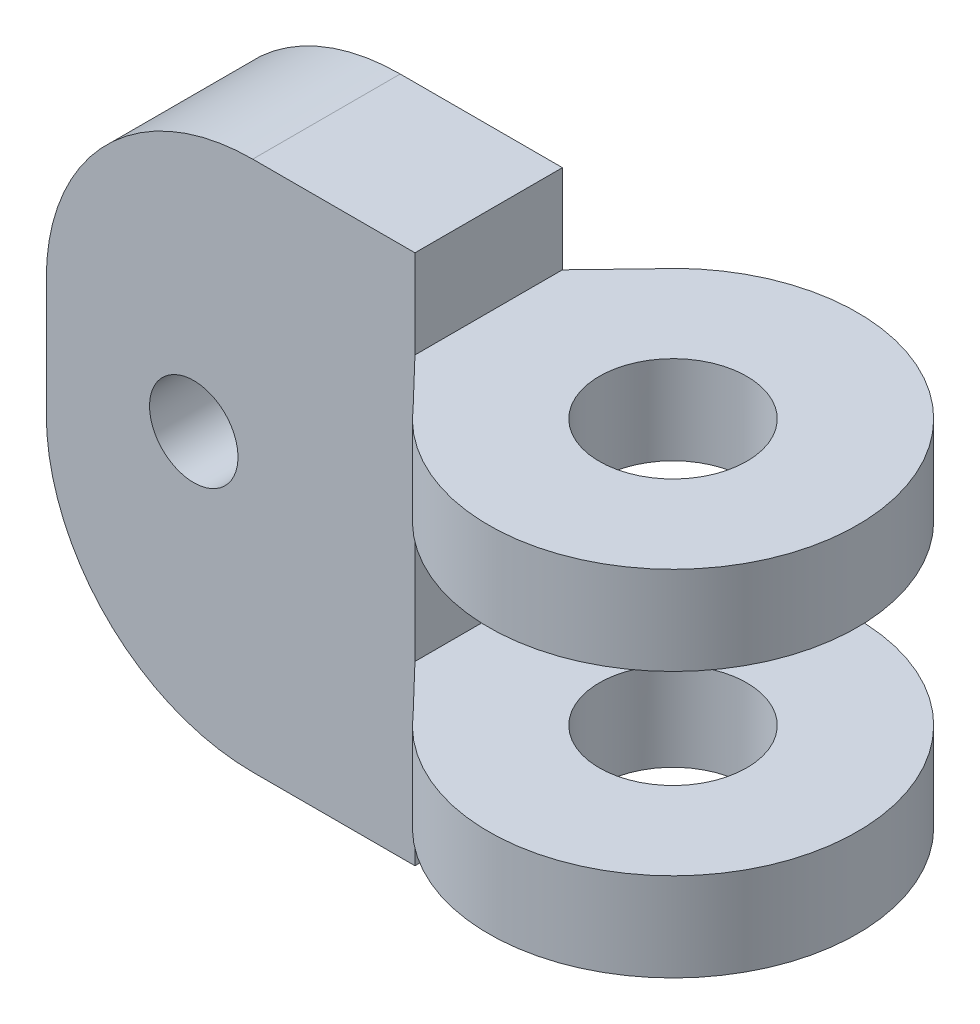
SolidWorks part; units mm, degrees
ref_plane "Alzado" through (0, 0, 0) normal (0, 0, 1) x (1, 0, 0)
ref_plane "Planta" through (0, 0, 0) normal (0, 1, 0) x (1, 0, 0)
ref_plane "Vista lateral" through (0, 0, 0) normal (1, 0, 0) x (0, 0, -1)
sketch "Croquis1" plane through (0, 0, 0) normal (0, 0, 1) x (1, 0, 0)
  line L0 (11.25, 17.1) -> (11.25, 14.1)
  line L1 (5.75, -0.9) -> (11.25, -0.9)
  line L2 (-1.25, 6.1) -> (-1.25, 10.1)
  line L3 (5.75, 17.1) -> (11.25, 17.1)
  line L4 (11.25, 11.1) -> (23.75, 11.1)
  line L5 (-1.25, -0.9) -> (1.25, 0.9) construction
  line L6 (-1.25, 17.1) -> (-1.0254, 14.0276) construction
  line L7 (11.25, 11.1) -> (11.25, 5.1)
  line L8 (-1.25, 8.1) -> (23.75, 8.1) construction
  line L9 (23.75, 5.1) -> (11.25, 5.1)
  line L10 (11.25, 2.1) -> (11.25, -0.9)
  line L11 (23.75, 11.1) -> (23.75, 14.1)
  line L12 (23.75, 14.1) -> (11.25, 14.1)
  line L13 (11.25, 17.1) -> (-1.25, 17.1) construction
  line L14 (23.75, 5.1) -> (23.75, 2.1)
  line L15 (23.75, 2.1) -> (11.25, 2.1)
  circle A0 centre (3.75, 8.1) radius 1.5
  arc A1 (-1.25, 10.1) -> (5.75, 17.1) centre (5.75, 10.1) cw
  arc A2 (5.75, -0.9) -> (-1.25, 6.1) centre (5.75, 6.1) cw
  point P0 (0, 0)
  dimension "D6" = 3
  dimension "D4" = 7
  dimension "D2" = 18
  dimension "D3" = 12.5
  dimension "D7" = 5
  dimension "D8" = 9
  dimension "D10" = 3
  dimension "D11" = 3
extrude "Saliente-Extruir1" add sketch "Croquis1" along normal blind 15
sketch "Croquis2" plane through (0, 0, 0) normal (0, 1, 0) x (1, 0, 0)
  line L0 (23.75, -7.5) -> (11.25, -7.5) construction
  line L1 (23.75, -7.5) -> (11.25, -7.5) construction
  line L2 (23.75, -15) -> (23.75, 0) construction
  line L3 (17.5, -1.25) -> (11.25, 0)
  line L4 (17.5, -13.75) -> (11.25, -15)
  line L5 (11.25, -15) -> (11.25, -17.9613)
  line L6 (11.25, -17.9613) -> (29.6635, -17.9613)
  line L7 (29.6635, -17.9613) -> (29.6635, 1.8686)
  line L8 (29.6635, 1.8686) -> (11.1263, 1.8686)
  line L9 (11.1263, 1.8686) -> (11.25, 0)
  line L10 (11.25, -15) -> (11.25, 0) construction
  line L11 (17.5, 0) -> (17.5, -15) construction
  line L12 (23.75, 0) -> (11.25, 0) construction
  line L13 (23.75, -15) -> (11.25, -15) construction
  circle A0 centre (17.5, -7.5) radius 2.5
  arc A1 (17.5, -13.75) -> (17.5, -1.25) centre (17.5, -7.5) ccw
  dimension "D1" = 5
extrude "Cortar-Extruir1" cut sketch "Croquis2" along normal blind 20
sketch "Croquis4" plane through (0, 17.1, 0) normal (0, 1, 0) x (1, 0, 0)
  line L0 (17.5, -1.25) -> (17.5, -13.75) construction
  line L1 (-1.25, -15) -> (-1.25, 0) construction
  line L2 (-4.3896, -10) -> (11.25, -10)
  line L4 (-4.3896, -5) -> (11.25, -5)
  line L5 (17.5, -1.25) -> (17.5, 1.8877)
  line L8 (11.25, -15) -> (11.25, 0) construction
  line L9 (11.25, -5) -> (13.2786, -2.891)
  line L10 (11.25, -10) -> (12.7402, -11.5505)
  line L11 (17.5, 1.8877) -> (-4.3896, 1.8877)
  line L12 (-4.3896, 1.8877) -> (-4.3896, -5)
  line L13 (-4.3896, -10) -> (-4.3896, -16.4565)
  line L14 (-4.3896, -16.4565) -> (17.5, -16.4565)
  line L15 (17.5, -16.4565) -> (17.5, -13.75)
  arc A0 (12.7402, -11.5505) -> (17.5, -13.75) centre (17.5, -7.5) ccw
  arc A1 (17.5, -1.25) -> (12.7307, -3.4607) centre (17.5, -7.5) ccw
  point P6 (-1.25, -7.5)
  line M1 (11.25, 0) -> (5.75, 0)
  line M2 (5.75, 0) -> (5.75, -15)
  line M3 (5.75, -15) -> (11.25, -15)
  line M4 (11.25, -15) -> (11.25, 0)
  dimension "D1" = 5
extrude "Cortar-Extruir2" cut sketch "Croquis4" against normal blind 26 contours A1 L5 L11 L12 L4 L9 M2 M1 M4 | L4 M2 M4 M1 | A0 L10 L2 L13 L14 L15 M4 M3 M2 | L2 M2 M3 M4
ref_plane "Plano1" through (0, 0, 7.5) normal (0, 0, 1) x (1, 0, 0)
